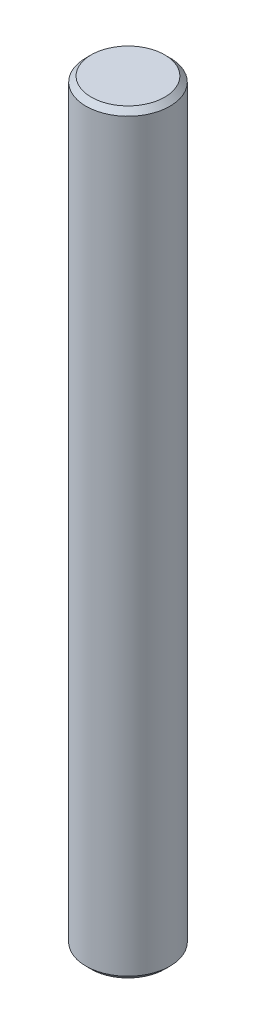
SolidWorks part; units mm, degrees
ref_plane "Front Plane" through (0, 0, 0) normal (0, 0, 1) x (1, 0, 0)
ref_plane "Top Plane" through (0, 0, 0) normal (0, 1, 0) x (1, 0, 0)
ref_plane "Right Plane" through (0, 0, 0) normal (1, 0, 0) x (0, 0, -1)
sketch "Sketch1" plane through (0, 0, 0) normal (0, 1, 0) x (1, 0, 0)
  circle A0 centre (0, 0) radius 4
  dimension "D1" = 8
extrude "Boss-Extrude1" add sketch "Sketch1" along normal mid plane 72
chamfer "Chamfer1" distance 0.5 angle 45 2 edges at (0, -36, 4) (0, 36, 4)
